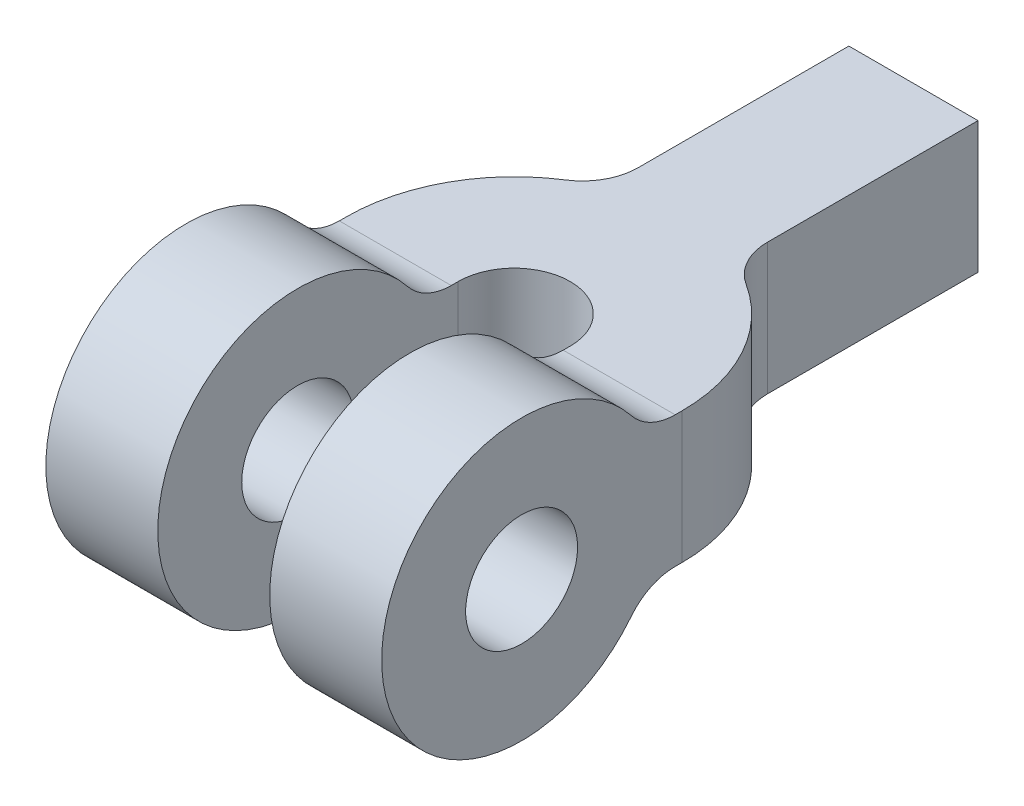
SolidWorks part; units mm, degrees
ref_plane "Front Plane" through (0, 0, 0) normal (0, 0, 1) x (1, 0, 0)
ref_plane "Top Plane" through (0, 0, 0) normal (0, 1, 0) x (1, 0, 0)
ref_plane "Right Plane" through (0, 0, 0) normal (1, 0, 0) x (0, 0, -1)
sketch "Sketch2" plane through (0, 0, 0) normal (0, 1, 0) x (1, 0, 0)
  line L1 (60, -125) -> (-60, -125)
  line L2 (60, -125) -> (60, 125)
  line L3 (60, 125) -> (-60, 125)
  line L4 (-60, -125) -> (-60, 125)
  line L5 (60, -125) -> (-60, 125) construction
  line L6 (60, 125) -> (-60, -125) construction
  point P0 (0, 0)
  dimension "D1" = 120
  dimension "D2" = 250
extrude "Boss-Extrude1" add sketch "Sketch2" along normal blind 100
sketch "Sketch3" plane through (0, 100, 0) normal (0, 1, 0) x (1, 0, 0)
  line L0 (0, 0) -> (0, 125) construction
  line L1 (60, 125) -> (-60, 125) construction
  line L2 (0, 0) -> (0, -125) construction
  line L3 (-60, -125) -> (60, -125) construction
  line L4 (-23.0717, 125) -> (-23.0717, 49.7707)
  line L5 (23.0717, 125) -> (23.0717, 49.7707)
  line L6 (-20, -17.6446) -> (-20, -125)
  line L7 (20, -17.6446) -> (20, -125)
  line L10 (-60, 125) -> (-60, -125)
  line L11 (-60, -125) -> (60, -125)
  line L12 (60, -125) -> (60, 125)
  line L13 (60, 125) -> (-60, 125)
  line L14 (-60, 125) -> (-60, -125)
  line L15 (-60, -125) -> (60, -125)
  line L16 (60, -125) -> (60, 125)
  line L17 (60, 125) -> (-60, 125)
  arc A0 (-32.3038, 32.9169) -> (32.3038, 32.9169) centre (0, -17.6446) ccw
  circle A1 centre (0, -17.6446) radius 20
  arc A2 (-32.3038, 32.9169) -> (-23.0717, 49.7707) centre (-43.0717, 49.7707) ccw
  arc A3 (32.3038, 32.9169) -> (23.0717, 49.7707) centre (43.0717, 49.7707) cw
  dimension "D1" = 40
  dimension "D2" = 120
  dimension "D4" = 20
  dimension "D5" = 20
  dimension "D3" = 0
sketch "Sketch4" plane through (0, 100, 0) normal (0, 1, 0) x (1, 0, 0)
  line L0 (-23.0717, 125) -> (-23.0717, 49.7707) construction
  line L1 (23.0717, 125) -> (23.0717, 49.7707) construction
  line L2 (20, -17.6446) -> (20, -125) construction
  line L3 (-20, -17.6446) -> (-20, -125) construction
  line L4 (-60, -125) -> (60, -125)
  line L5 (60, -125) -> (60, 125)
  line L6 (60, 125) -> (-60, 125)
  line L7 (-60, 125) -> (-60, -125)
  line L8 (-60, -125) -> (60, -125)
  line L9 (60, -125) -> (60, 125)
  line L10 (60, 125) -> (-60, 125)
  line L11 (-60, 125) -> (-60, -125)
  line L12 (-23.0717, 125) -> (-23.0717, 49.7707)
  line L13 (23.0717, 125) -> (23.0717, 49.7707)
  line L14 (20, -17.6446) -> (20, -125)
  line L15 (-20, -17.6446) -> (-20, -125)
  arc A0 (-32.3038, 32.9169) -> (-23.0717, 49.7707) centre (-43.0717, 49.7707) ccw construction
  circle A1 centre (0, -17.6446) radius 20
  circle A2 centre (0, -17.6446) radius 20
  arc A3 (-32.3038, 32.9169) -> (32.3038, 32.9169) centre (0, -17.6446) ccw construction
  arc A4 (23.0717, 49.7707) -> (32.3038, 32.9169) centre (43.0717, 49.7707) ccw construction
  arc A5 (-32.3038, 32.9169) -> (-23.0717, 49.7707) centre (-43.0717, 49.7707) ccw
  arc A6 (-32.3038, 32.9169) -> (32.3038, 32.9169) centre (0, -17.6446) ccw
  arc A7 (23.0717, 49.7707) -> (32.3038, 32.9169) centre (43.0717, 49.7707) ccw
  line M6 (-60, 125) -> (-60, -125)
  line M9 (60, 125) -> (-60, 125)
  dimension "D1" = 0
  dimension "D2" = 0
extrude "Cut-Extrude1" cut sketch "Sketch4" against normal blind 100 contours A6 A5 L12 L10 M6 | L13 A7 A6 L9 M9 | A2 | L15 A6 L14 A2 | A6 L15 L8 L14
sketch "Sketch5" plane through (60, 0, 0) normal (1, 0, 0) x (0, 0, -1)
  line L0 (-125, 100) -> (-125, 0) construction
  line L1 (-125, 0) -> (-17.6446, 0) construction
  line L2 (125, 73.475) -> (125, 26.525)
  line L3 (-20.1372, 73.475) -> (125, 73.475)
  line L4 (125, 0) -> (125, 100) construction
  line L5 (-75, 50) -> (125, 50) construction
  line L6 (-20.1372, 26.525) -> (125, 26.525)
  line L7 (125, 100) -> (49.7707, 100) construction
  line L8 (49.7707, 0) -> (125, 0) construction
  line L9 (49.7707, 100) -> (32.9169, 100) construction
  line L10 (32.9169, 0) -> (49.7707, 0) construction
  line L11 (32.9169, 100) -> (-17.6446, 100) construction
  line L12 (-17.6446, 0) -> (32.9169, 0) construction
  line L13 (-17.6446, 100) -> (-125, 100) construction
  line L14 (125, 100) -> (49.7707, 100)
  line L15 (49.7707, 0) -> (125, 0)
  line L16 (125, 0) -> (125, 100)
  line L17 (49.7707, 100) -> (32.9169, 100)
  line L18 (32.9169, 0) -> (49.7707, 0)
  line L19 (32.9169, 100) -> (-17.6446, 100)
  line L20 (-17.6446, 0) -> (32.9169, 0)
  line L21 (-125, 0) -> (-17.6446, 0)
  line L22 (-17.6446, 100) -> (-125, 100)
  line L23 (-125, 100) -> (-125, 0)
  arc A0 (-35.8123, 81.0536) -> (-35.8123, 18.9464) centre (-75, 50) ccw
  circle A1 centre (-75, 50) radius 20
  arc A2 (-20.1372, 73.475) -> (-35.8123, 81.0536) centre (-20.1372, 93.475) cw
  arc A3 (-20.1372, 26.525) -> (-35.8123, 18.9464) centre (-20.1372, 6.525) ccw
  dimension "D2" = 100
  dimension "D3" = 20
  dimension "D4" = 20
  dimension "D1" = 50
extrude "Cut-Extrude5" cut sketch "Sketch5" against normal through all
